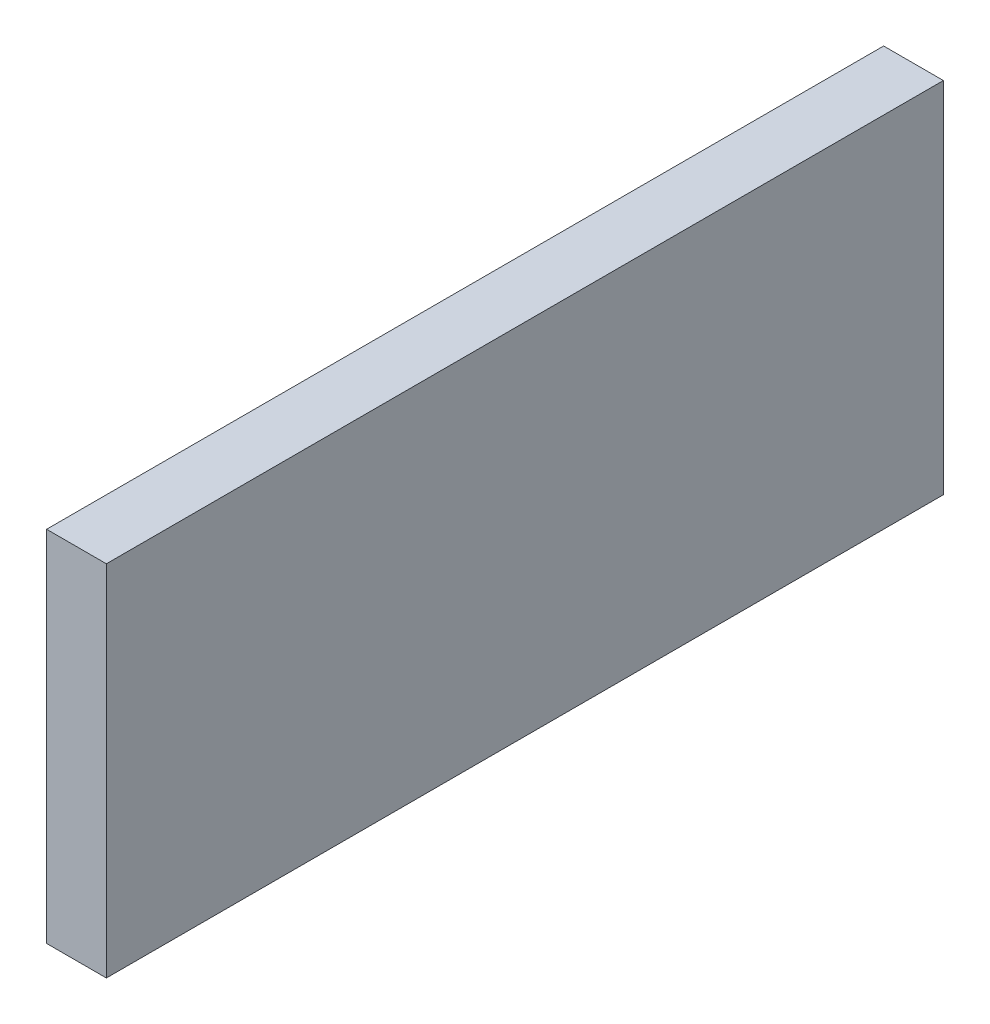
SolidWorks part; units mm, degrees
ref_plane "Front Plane" through (0, 0, 0) normal (0, 0, 1) x (1, 0, 0)
ref_plane "Top Plane" through (0, 0, 0) normal (0, 1, 0) x (1, 0, 0)
ref_plane "Right Plane" through (0, 0, 0) normal (1, 0, 0) x (0, 0, -1)
sketch "Sketch1" plane through (0, 6.8129, -4.8498) normal (1, 0, 0) x (0, 0, -1)
  line L1 (-15.6141, 16.0277) -> (19.3859, 16.0277)
  line L2 (-15.6141, 16.0277) -> (-15.6141, 1.0277)
  line L3 (-15.6141, 1.0277) -> (19.3859, 1.0277)
  line L4 (19.3859, 16.0277) -> (19.3859, 1.0277)
  dimension "D1" = 35
  dimension "D2" = 15
extrude "Boss-Extrude1" add sketch "Sketch1" along normal blind 2.5
